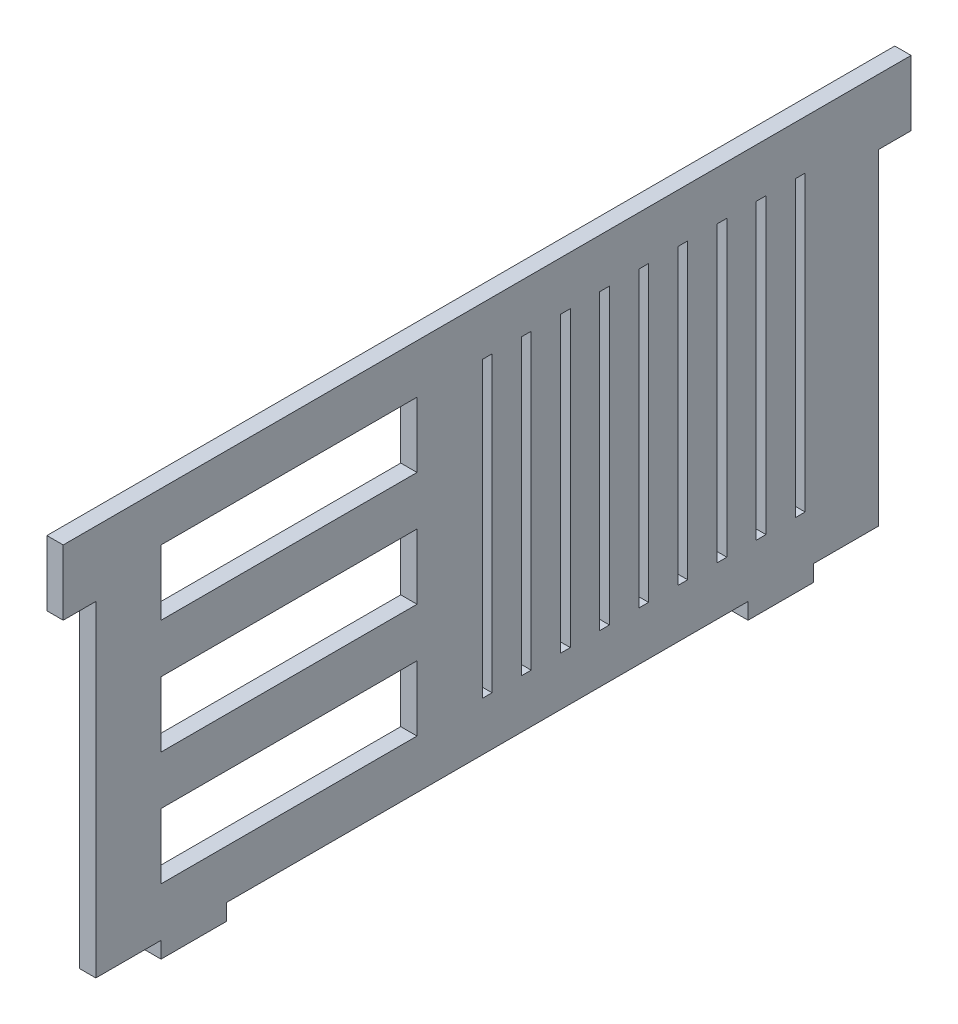
SolidWorks part; units mm, degrees
material "Perspex (TM) GS Acrylic Cast Sheet"
ref_plane "Ebene vorne" through (0, 0, 0) normal (0, 0, 1) x (1, 0, 0)
ref_plane "Ebene oben" through (0, 0, 0) normal (0, 1, 0) x (1, 0, 0)
ref_plane "Ebene rechts" through (0, 0, 0) normal (1, 0, 0) x (0, 0, -1)
sketch "Skizze2" plane through (0, 0, 0) normal (1, 0, 0) x (0, 0, -1)
  line L1 (-120, 60) -> (120, 60)
  line L2 (-120, 60) -> (-120, -60)
  line L3 (-120, -60) -> (120, -60)
  line L4 (120, 60) -> (120, -60)
  line L5 (-120, 60) -> (120, -60) construction
  line L6 (-120, -60) -> (120, 60) construction
  line L7 (-120, 60) -> (-130, 60)
  line L8 (-120, 60) -> (-120, 40)
  line L9 (-120, 40) -> (-130, 40)
  line L10 (-130, 60) -> (-130, 40)
  line L11 (-120, 60) -> (-130, 40) construction
  line L12 (-120, 40) -> (-130, 60) construction
  line L13 (120, 60) -> (130, 60)
  line L14 (120, 60) -> (120, 40)
  line L15 (120, 40) -> (130, 40)
  line L16 (130, 60) -> (130, 40)
  line L17 (120, 60) -> (130, 40) construction
  line L18 (120, 40) -> (130, 60) construction
  line L19 (100, -60) -> (80, -60)
  line L20 (100, -60) -> (100, -65)
  line L21 (100, -65) -> (80, -65)
  line L22 (80, -60) -> (80, -65)
  line L23 (-80, -60) -> (-100, -60)
  line L24 (-80, -60) -> (-80, -65)
  line L25 (-80, -65) -> (-100, -65)
  line L26 (-100, -60) -> (-100, -65)
  point P0 (0, 0)
  point P9 (-125, 50)
  point P13 (125, 50)
  dimension "D1" = 240
  dimension "D2" = 120
  dimension "D3" = 10
  dimension "D4" = 20
  dimension "D5" = 20
  dimension "D6" = 20
  dimension "D7" = 5
  dimension "D8" = 20
extrude "Aufsatz-Linear austragen1" add sketch "Skizze2" along normal blind 5
sketch "Skizze3" plane through (0, 0, 0) normal (-1, 0, 0) x (0, 0, 1)
  line L0 (80, -60) -> (-80, -60) construction
  line L1 (-1.5, 45) -> (1.5, 45)
  line L2 (-1.5, 45) -> (-1.5, -45)
  line L3 (-1.5, -45) -> (1.5, -45)
  line L4 (1.5, 45) -> (1.5, -45)
  line L5 (-1.5, 45) -> (1.5, -45) construction
  line L6 (-1.5, -45) -> (1.5, 45) construction
  point P0 (0, 0)
  dimension "D1" = 3
  dimension "D2" = 15
extrude "Schnitt-Linear austragen1" cut sketch "Skizze3" against normal through all
pattern_linear "Lineares Muster1" count 9 spacing 12 along (0, 0, -1) of "Schnitt-Linear austragen1"
sketch "Skizze4" plane through (0, 0, 0) normal (-1, 0, 0) x (0, 0, 1)
  line L0 (60.75, 0) -> (0, 0) construction
  line L1 (100, 10) -> (21.5, 10)
  line L2 (100, 10) -> (100, -10)
  line L3 (100, -10) -> (21.5, -10)
  line L4 (21.5, 10) -> (21.5, -10)
  line L5 (100, 10) -> (21.5, -10) construction
  line L6 (100, -10) -> (21.5, 10) construction
  line L7 (1.5, -45) -> (1.5, 45) construction
  line L8 (120, 40) -> (120, -60) construction
  line L9 (1.5, 45) -> (130, 45) construction
  line L10 (130, 60) -> (130, 40) construction
  line L11 (1.5, -45) -> (120, -45) construction
  line L13 (21.5, -45) -> (100, -45)
  line L14 (21.5, -45) -> (21.5, -25)
  line L15 (21.5, -25) -> (100, -25)
  line L16 (100, -45) -> (100, -25)
  line L17 (21.5, -45) -> (100, -25) construction
  line L18 (21.5, -25) -> (100, -45) construction
  line L19 (100, 45) -> (21.5, 45)
  line L20 (100, 45) -> (100, 25)
  line L21 (100, 25) -> (21.5, 25)
  line L22 (21.5, 45) -> (21.5, 25)
  line L23 (100, 45) -> (21.5, 25) construction
  line L24 (100, 25) -> (21.5, 45) construction
  point P0 (60.75, 0)
  point P24 (60.75, -35)
  point P29 (60.75, 35)
  dimension "D1" = 20
  dimension "D2" = 20
  dimension "D3" = 20
extrude "Schnitt-Linear austragen2" cut sketch "Skizze4" against normal through all
